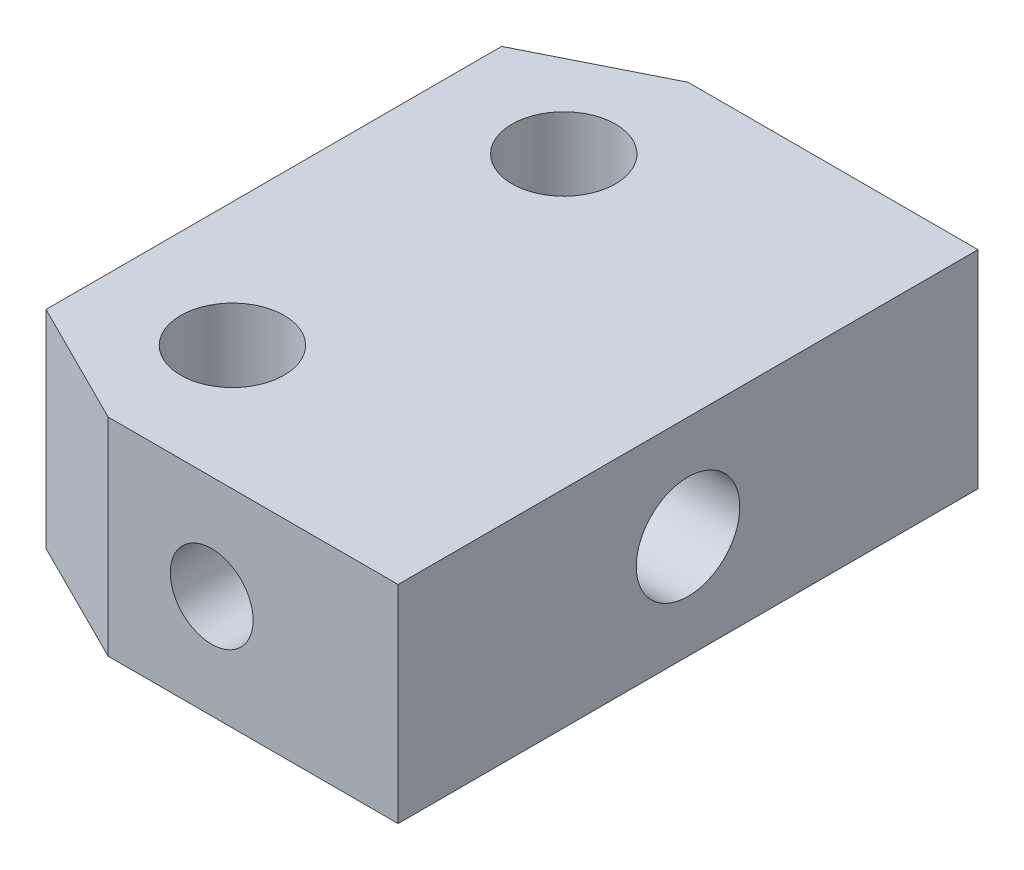
SolidWorks part; units mm, degrees
ref_plane "前视基准面" through (0, 0, 0) normal (0, 0, 1) x (1, 0, 0)
ref_plane "上视基准面" through (0, 0, 0) normal (0, 1, 0) x (1, 0, 0)
ref_plane "右视基准面" through (0, 0, 0) normal (1, 0, 0) x (0, 0, -1)
ref_plane "基准面4" through (0, -65, 0) normal (0, 1, 0) x (1, 0, 0)
sketch "草图1" plane through (0, -65, 0) normal (0, 1, 0) x (1, 0, 0)
  line L0 (50, 19.5) -> (70, 19.5)
  line L1 (70, 19.5) -> (70, 47.5)
  line L2 (70, 47.5) -> (50, 47.5)
  line L3 (50, 47.5) -> (50, 19.5)
extrude "凸台-拉伸1" add sketch "草图1" against normal blind 10
hole_wizard "Ø5.0 (5) 直径孔1" positions "草图3" profile "草图2" hole size "Ø5.0" standard "ANSI Metric"
sketch "草图3" plane through (0, -75, 0) normal (0, -1, 0) x (-1, 0, 0)
  point P0 (-56, 25.5)
  point P1 (-56, 41.5)
sketch "草图2" plane through (56, -75, -25.5) normal (1, 0, 0) x (0, 0, -1)
  line L0 (0, 0) -> (0, 10)
  line L1 (0, 10) -> (2.5, 10)
  line L2 (2.5, 10) -> (2.5, 0)
  line L5 (2.5, 0) -> (0, 0)
  line L11 (0, -6.35) -> (0, 107.95) construction
  dimension "通孔孔直径" = 5
  dimension "通孔孔深度" = 10
hole_wizard "Ø5.0 (5) 直径孔2" positions "草图5" profile "草图4" hole size "Ø5.0" standard "ANSI Metric"
sketch "草图5" plane through (50, 0, 0) normal (-1, 0, 0) x (0, 0, 1)
  point P0 (-33.5, -70)
sketch "草图4" plane through (50, -70, -33.5) normal (0, 1, 0) x (0, 0, 1)
  line L0 (0, 0) -> (0, 20)
  line L1 (0, 20) -> (2.5, 20)
  line L2 (2.5, 20) -> (2.5, 0)
  line L5 (2.5, 0) -> (0, 0)
  line L11 (0, -6.35) -> (0, 107.95) construction
  dimension "通孔孔直径" = 5
  dimension "通孔孔深度" = 20
hole_wizard "Ø4.0 (4) 直径孔1" positions "草图7" profile "草图6" hole size "Ø4.0" standard "ANSI Metric"
sketch "草图7" plane through (0, 0, -47.5) normal (0, 0, -1) x (-1, 0, 0)
  point P0 (-61, -70)
sketch "草图6" plane through (61, -70, -47.5) normal (1, 0, 0) x (0, 1, 0)
  line L0 (0, 0) -> (0, 40.5)
  line L1 (0, 40.5) -> (2, 40.5)
  line L2 (2, 40.5) -> (2, 0)
  line L5 (2, 0) -> (0, 0)
  line L10 (0, 40.5) -> (-2, 40.5) construction
  line L11 (0, -6.35) -> (0, 107.95) construction
  dimension "孔直径" = 4
  dimension "孔深度" = 40.5
  dimension "导头角度" = 180
chamfer "倒角1" distance 3 angle 63.435 2 edges at (50, -70, -19.5) (50, -70, -47.5)
